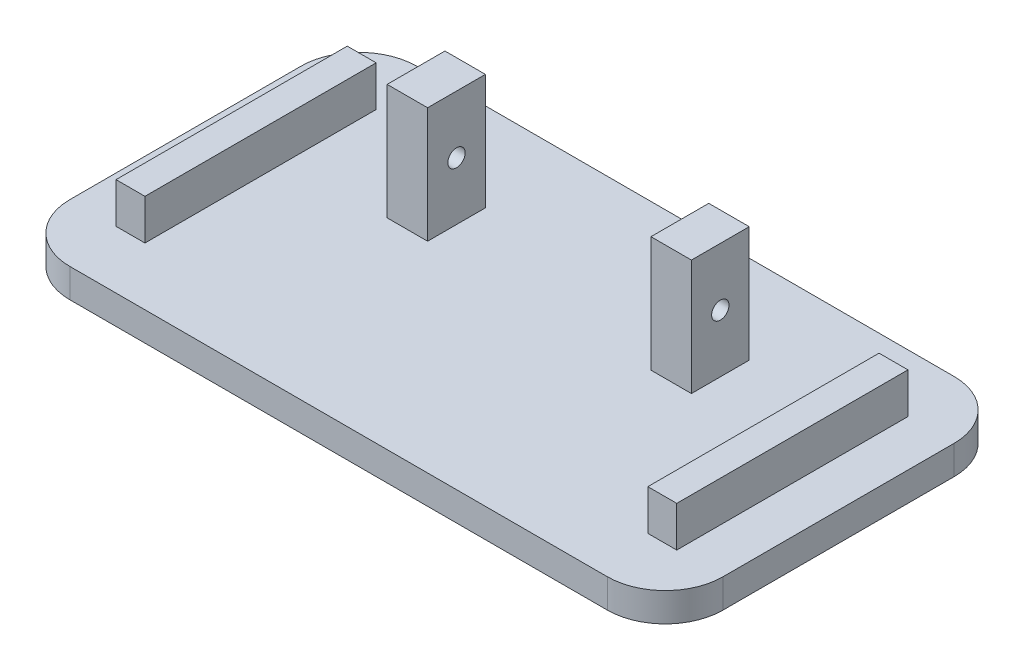
SolidWorks part; units mm, degrees
material "ABS"
ref_plane "Plano frontal" through (0, 0, 0) normal (0, 0, 1) x (1, 0, 0)
ref_plane "Plano superior" through (0, 0, 0) normal (0, 1, 0) x (1, 0, 0)
ref_plane "Plano direito" through (0, 0, 0) normal (1, 0, 0) x (0, 0, -1)
sketch "Esboço1" plane through (0, 0, 0) normal (0, 1, 0) x (1, 0, 0)
  line L1 (-13.2145, 15.5332) -> (79.7855, 15.5332)
  line L2 (-23.2145, 5.5332) -> (-23.2145, -34.4668)
  line L3 (-13.2145, -44.4668) -> (79.7855, -44.4668)
  line L4 (89.7855, 5.5332) -> (89.7855, -34.4668)
  arc A0 (89.7855, 5.5332) -> (79.7855, 15.5332) centre (79.7855, 5.5332) ccw
  arc A1 (89.7855, -34.4668) -> (79.7855, -44.4668) centre (79.7855, -34.4668) cw
  arc A2 (-13.2145, -44.4668) -> (-23.2145, -34.4668) centre (-13.2145, -34.4668) cw
  arc A3 (-23.2145, 5.5332) -> (-13.2145, 15.5332) centre (-13.2145, 5.5332) cw
  point P4 (33.2855, 15.5332)
  point P7 (89.7855, 15.5332)
  point P12 (-23.2145, -44.4668)
  point P15 (-23.2145, 15.5332)
  dimension "D4" = 10
  dimension "D1" = 113
  dimension "D2" = 56.5
  dimension "D3" = 60
extrude "Ressalto-extrusão1" add sketch "Esboço1" along normal blind 5
sketch "Esboço2" plane through (0, 5, 0) normal (0, 1, 0) x (1, 0, 0)
  line L0 (89.7855, -34.4668) -> (89.7855, 5.5332) construction
  line L1 (-3.0345, -9.7476) -> (-3.0345, 0.2524) construction
  line L2 (69.6055, -9.7476) -> (69.6055, 0.2524) construction
  line L3 (-3.0345, -9.7476) -> (69.6055, -9.7476) construction
  line L4 (-3.0345, 0.2524) -> (69.6055, 0.2524) construction
  line L5 (52.6055, 0.2524) -> (52.6055, -9.7476)
  line L6 (6.9655, 0.2524) -> (13.9655, 0.2524)
  line L7 (6.9655, -9.7476) -> (13.9655, -9.7476)
  line L8 (6.9655, 0.2524) -> (6.9655, -9.7476)
  line L9 (13.9655, 0.2524) -> (13.9655, -9.7476)
  line L10 (59.6055, 0.2524) -> (59.6055, -9.7476)
  line L11 (52.6055, 0.2524) -> (59.6055, 0.2524)
  line L12 (52.6055, -9.7476) -> (59.6055, -9.7476)
  point P8 (6.9655, -4.7476)
  dimension "D1" = 10
  dimension "D2" = 7
  dimension "D3" = 10
  dimension "D4" = 20.18
  dimension "D5" = 7
extrude "Ressalto-extrusão2" add sketch "Esboço2" along normal blind 20
sketch "Esboço4" plane through (6.9655, 0, 0) normal (-1, 0, 0) x (0, 0, 1)
  line L0 (-0.2524, 5) -> (9.7476, 5) construction
  line L1 (9.7476, 25) -> (9.7476, 5) construction
  circle A0 centre (4.7476, 15) radius 1.5
  dimension "D1" = 10
  dimension "D2" = 5
extrude "Corte-extrusão1" cut sketch "Esboço4" against normal through all
sketch "Esboço5" plane through (0, 5, 0) normal (0, 1, 0) x (1, 0, 0)
  line L0 (79.7855, 15.5332) -> (-13.2145, 15.5332) construction
  line L1 (-15.2145, 5.5332) -> (-10.2145, 5.5332)
  line L2 (-15.2145, 5.5332) -> (-15.2145, -34.4668)
  line L3 (-15.2145, -34.4668) -> (-10.2145, -34.4668)
  line L4 (-10.2145, 5.5332) -> (-10.2145, -34.4668)
  line L5 (-13.2145, -44.4668) -> (79.7855, -44.4668) construction
  line L6 (-23.2145, 5.5332) -> (-23.2145, -34.4668) construction
  line L7 (89.7855, -34.4668) -> (89.7855, 5.5332) construction
  line L8 (76.7855, 5.5332) -> (81.7855, 5.5332)
  line L9 (76.7855, 5.5332) -> (76.7855, -34.4668)
  line L10 (76.7855, -34.4668) -> (81.7855, -34.4668)
  line L11 (81.7855, 5.5332) -> (81.7855, -34.4668)
  dimension "D1" = 10
  dimension "D2" = 10
  dimension "D3" = 8
  dimension "D4" = 40
  dimension "D5" = 10
  dimension "D6" = 8
extrude "Ressalto-extrusão3" add sketch "Esboço5" along normal blind 7
